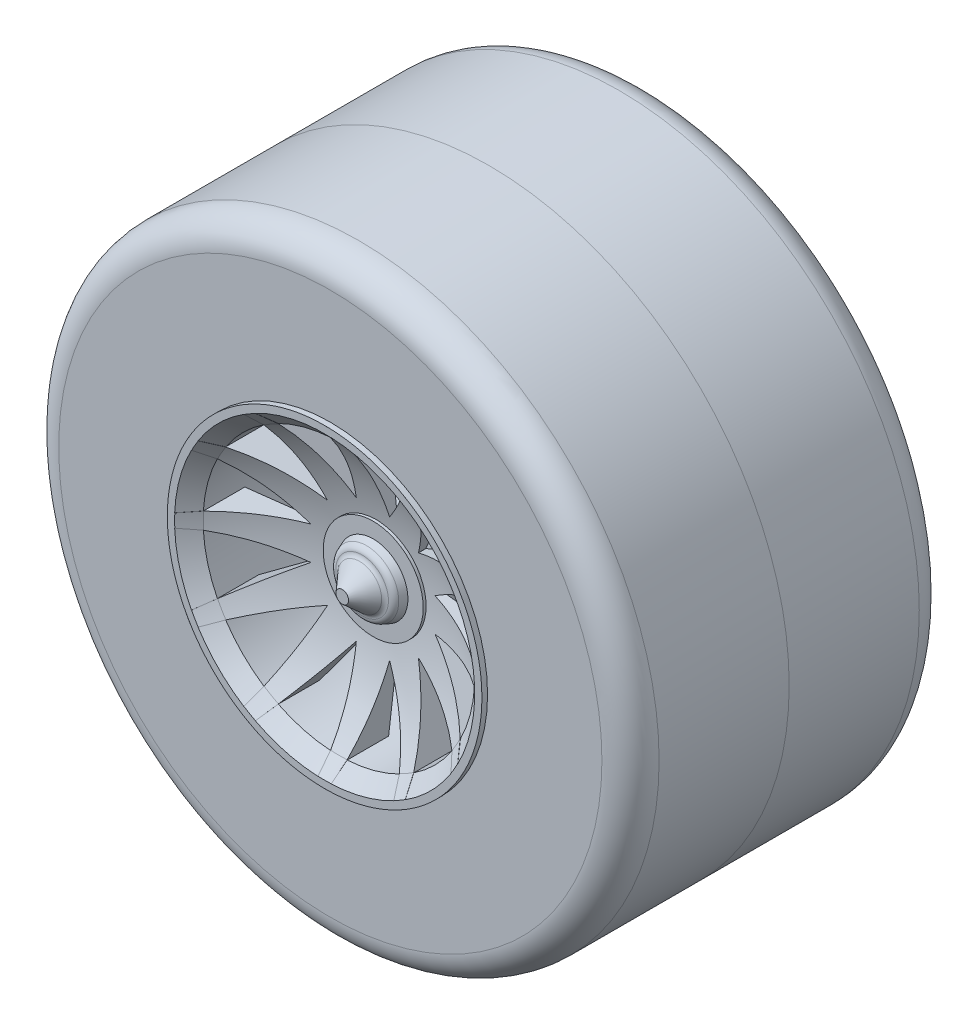
SolidWorks part; units mm, degrees
ref_plane "Front Plane" through (0, 0, 0) normal (0, 0, 1) x (1, 0, 0)
ref_plane "Top Plane" through (0, 0, 0) normal (0, 1, 0) x (1, 0, 0)
ref_plane "Right Plane" through (0, 0, 0) normal (1, 0, 0) x (0, 0, -1)
sketch "Sketch1" plane through (0, 0, 0) normal (1, 0, 0) x (0, 0, -1)
  line L0 (0, 0) -> (0, 21)
  line L1 (0, 21) -> (-9.1, 21)
  line L2 (-11.1, 19) -> (-11.1, 11)
  line L3 (-11.1, 11) -> (-11.5, 11)
  line L4 (-11.5, 11) -> (-11.5, 0)
  line L5 (-11.5, 0) -> (0, 0)
  arc A0 (-11.1, 19) -> (-9.1, 21) centre (-9.1, 19) cw
  dimension "D5" = 2
  dimension "D1" = 21
  dimension "D2" = 0.4
  dimension "D3" = 11.5
  dimension "D4" = 11
revolve "Revolve1" add sketch "Sketch1" angle 360 about L5
sketch "Sketch3" plane through (0, 0, 11.5) normal (0, 0, 1) x (1, 0, 0)
  circle A0 centre (0, 0) radius 9.5
  dimension "D1" = 19
extrude "Cut-Extrude3" cut sketch "Sketch3" against normal through all both and the other way through all
chamfer "Chamfer1" distance 1 angle 45 1 edges at (-9.5, 0, 11.5)
sketch "Sketch4" plane through (0, 0, 11.1) normal (0, 0, 1) x (1, 0, 0)
  line L0 (0, 4.5) -> (0, 21) construction
  line L1 (-0.4251, 10.8203) -> (-1.1632, 4.3471)
  line L2 (0.4251, 10.8203) -> (1.1632, 4.3471)
  line L3 (5.042, 9.5832) -> (1.1662, 4.3463)
  line L4 (5.7783, 9.1581) -> (3.1809, 3.1831)
  line L5 (9.1581, 5.7783) -> (3.1831, 3.1809)
  line L6 (9.5832, 5.042) -> (4.3463, 1.1662)
  line L7 (10.8203, 0.4251) -> (4.3471, 1.1632)
  line L8 (10.8203, -0.4251) -> (4.3471, -1.1632)
  line L9 (9.5832, -5.042) -> (4.3463, -1.1662)
  line L10 (9.1581, -5.7783) -> (3.1831, -3.1809)
  line L11 (5.7783, -9.1581) -> (3.1809, -3.1831)
  line L12 (5.042, -9.5832) -> (1.1662, -4.3463)
  line L13 (0.4251, -10.8203) -> (1.1632, -4.3471)
  line L14 (-0.4251, -10.8203) -> (-1.1632, -4.3471)
  line L15 (-5.042, -9.5832) -> (-1.1662, -4.3463)
  line L16 (-5.7783, -9.1581) -> (-3.1809, -3.1831)
  line L17 (-9.1581, -5.7783) -> (-3.1831, -3.1809)
  line L18 (-9.5832, -5.042) -> (-4.3463, -1.1662)
  line L19 (-10.8203, -0.4251) -> (-4.3471, -1.1632)
  line L20 (-10.8203, 0.4251) -> (-4.3471, 1.1632)
  line L21 (-9.5832, 5.042) -> (-4.3463, 1.1662)
  line L22 (-9.1581, 5.7783) -> (-3.2024, 3.1893)
  line L23 (-5.7783, 9.1581) -> (-3.1893, 3.2024)
  line L24 (-5.042, 9.5832) -> (-1.1662, 4.3463)
  arc A0 (-9.4089, 5.6984) -> (-9.6395, 5.2991) centre (0, 0) ccw
  arc A1 (-4.3463, 1.1662) -> (-4.3471, 1.1632) centre (0, 0) ccw
  circle A2 centre (0, 0) radius 21 construction
  arc A3 (-5.2991, 9.6395) -> (-5.6984, 9.4089) centre (0, 0) ccw
  arc A4 (0.2305, 10.9976) -> (-0.2305, 10.9976) centre (0, 0) ccw
  arc A5 (5.6984, 9.4089) -> (5.2991, 9.6395) centre (0, 0) ccw
  arc A6 (9.6395, 5.2991) -> (9.4089, 5.6984) centre (0, 0) ccw
  arc A7 (10.9976, -0.2305) -> (10.9976, 0.2305) centre (0, 0) ccw
  arc A8 (9.4089, -5.6984) -> (9.6395, -5.2991) centre (0, 0) ccw
  arc A9 (5.2991, -9.6395) -> (5.6984, -9.4089) centre (0, 0) ccw
  arc A10 (-0.2305, -10.9976) -> (0.2305, -10.9976) centre (0, 0) ccw
  arc A11 (-5.6984, -9.4089) -> (-5.2991, -9.6395) centre (0, 0) ccw
  arc A12 (-9.6395, -5.2991) -> (-9.4089, -5.6984) centre (0, 0) ccw
  arc A13 (-10.9976, 0.2305) -> (-10.9976, -0.2305) centre (0, 0) ccw
  arc A14 (-3.1809, 3.1831) -> (-3.1831, 3.1809) centre (0, 0) ccw
  arc A15 (-1.1632, 4.3471) -> (-1.1662, 4.3463) centre (0, 0) ccw
  arc A16 (1.1662, 4.3463) -> (1.1632, 4.3471) centre (0, 0) ccw
  arc A17 (3.1831, 3.1809) -> (3.1809, 3.1831) centre (0, 0) ccw
  arc A18 (4.3471, 1.1632) -> (4.3463, 1.1662) centre (0, 0) ccw
  arc A19 (-4.3471, -1.1632) -> (-4.3463, -1.1662) centre (0, 0) ccw
  arc A20 (-3.1831, -3.1809) -> (-3.1809, -3.1831) centre (0, 0) ccw
  arc A21 (-1.1662, -4.3463) -> (-1.1632, -4.3471) centre (0, 0) ccw
  arc A22 (1.1632, -4.3471) -> (1.1662, -4.3463) centre (0, 0) ccw
  arc A23 (3.1809, -3.1831) -> (3.1831, -3.1809) centre (0, 0) ccw
  arc A24 (4.3463, -1.1662) -> (4.3471, -1.1632) centre (0, 0) ccw
  arc A25 (-5.042, 9.5832) -> (-5.2991, 9.6395) centre (-5.2028, 9.4642) ccw
  arc A26 (-5.7783, 9.1581) -> (-5.6984, 9.4089) centre (-5.5948, 9.2378) cw
  arc A27 (-9.1581, 5.7783) -> (-9.4089, 5.6984) centre (-9.2378, 5.5948) ccw
  arc A28 (-9.5832, 5.042) -> (-9.6395, 5.2991) centre (-9.4642, 5.2028) cw
  arc A29 (-10.8203, 0.4251) -> (-10.9976, 0.2305) centre (-10.7976, 0.2264) ccw
  arc A30 (-10.8203, -0.4251) -> (-10.9976, -0.2305) centre (-10.7976, -0.2264) cw
  arc A31 (-9.5832, -5.042) -> (-9.6395, -5.2991) centre (-9.4642, -5.2028) ccw
  arc A32 (-9.1581, -5.7783) -> (-9.4089, -5.6984) centre (-9.2378, -5.5948) cw
  arc A33 (-5.7783, -9.1581) -> (-5.6984, -9.4089) centre (-5.5948, -9.2378) ccw
  arc A34 (-5.042, -9.5832) -> (-5.2991, -9.6395) centre (-5.2028, -9.4642) cw
  arc A35 (-0.4251, -10.8203) -> (-0.2305, -10.9976) centre (-0.2264, -10.7976) ccw
  arc A36 (0.4251, -10.8203) -> (0.2305, -10.9976) centre (0.2264, -10.7976) cw
  arc A37 (5.042, -9.5832) -> (5.2991, -9.6395) centre (5.2028, -9.4642) ccw
  arc A38 (5.7783, -9.1581) -> (5.6984, -9.4089) centre (5.5948, -9.2378) cw
  arc A39 (9.1581, -5.7783) -> (9.4089, -5.6984) centre (9.2378, -5.5948) ccw
  arc A40 (9.5832, -5.042) -> (9.6395, -5.2991) centre (9.4642, -5.2028) cw
  arc A41 (10.8203, -0.4251) -> (10.9976, -0.2305) centre (10.7976, -0.2264) ccw
  arc A42 (10.8203, 0.4251) -> (10.9976, 0.2305) centre (10.7976, 0.2264) cw
  arc A43 (9.5832, 5.042) -> (9.6395, 5.2991) centre (9.4642, 5.2028) ccw
  arc A44 (9.1581, 5.7783) -> (9.4089, 5.6984) centre (9.2378, 5.5948) cw
  arc A45 (5.7783, 9.1581) -> (5.6984, 9.4089) centre (5.5948, 9.2378) ccw
  arc A46 (5.042, 9.5832) -> (5.2991, 9.6395) centre (5.2028, 9.4642) cw
  arc A47 (0.4251, 10.8203) -> (0.2305, 10.9976) centre (0.2264, 10.7976) ccw
  arc A48 (-0.4251, 10.8203) -> (-0.2305, 10.9976) centre (-0.2264, 10.7976) cw
  arc A49 (-3.1893, 3.2024) -> (-3.2024, 3.1893) centre (-3.1984, 3.1984) cw
  point P57 (0, 0)
  point P101 (0.4054, 10.9925)
  point P104 (-0.4054, 10.9925)
  dimension "D1" = 22
  dimension "D2" = 9
  dimension "D4" = 0.2
  dimension "D5" = 0.01
  dimension "D3" = 12
extrude "Boss-Extrude1" add sketch "Sketch4" along normal blind 10 and the other way blind 3.5
sketch "Sketch5" plane through (0, 0, 0) normal (1, 0, 0) x (0, 0, -1)
  line L0 (0, 0) -> (-34.6228, 0) construction
  line L1 (-10.5, 9.4824) -> (-11.5, 10.4898)
  line L2 (-11.5, 10.4898) -> (-11.5, 10.9976)
  line L3 (-11.5, 10.9976) -> (-11.8812, 11.6153)
  line L4 (-11.8812, 11.6153) -> (-21.6946, 11.6153)
  line L5 (-21.6946, 11.6153) -> (-21.6946, 0)
  line L6 (-21.6946, 0) -> (-7.5497, 0)
  spline S0 degree 2 poles (-10.5, 9.4824) (-7.6252, 5.7251) (-7.5497, 0) knots 0 0 0 1 1 1
revolve "Cut-Revolve1" cut sketch "Sketch5" angle 360 about L6
sketch "Sketch6" plane through (0, 0, 0) normal (1, 0, 0) x (0, 0, -1)
  line L0 (0, 0) -> (-21.6266, 0) construction
  line L1 (0, -21) -> (0, 21) construction
  line L2 (-7.4322, 0) -> (-7.9181, 2.5)
  line L3 (-7.9181, 2.5) -> (-8.8749, 2.128)
  line L4 (-8.8749, 2.128) -> (-8.8749, 1.6817)
  line L5 (-8.8749, 1.6817) -> (-10.2635, 0.4419)
  line L6 (-10.2635, 0.4419) -> (-10.2635, 0)
  line L7 (-10.2635, 0) -> (-7.4322, 0)
  dimension "D1" = 2.5
  dimension "D2" = 101
revolve "Revolve2" add sketch "Sketch6" angle 360 about L0
fillet "Fillet1" radius 0.5 1 edges at (-1.6817, 0, 8.8749)
fillet "Fillet2" radius 0.5 1 edges at (-2.128, 0, 8.8749)
mirror "Mirror1" about plane through (0, 0, 0) normal (0, 0, 1) of bodies 104 105
sketch "Sketch7" plane through (0, 0, 11.1) normal (0, 0, 1) x (1, 0, 0)
  circle A0 centre (0, 0) radius 3.5
  dimension "D1" = 7
extrude "Boss-Extrude2" add sketch "Sketch7" against normal blind 15 from offset 3 offset against normal yes
sketch "Sketch8" plane through (0, 0, -11.1) normal (0, 0, -1) x (-1, 0, 0)
  circle A0 centre (0, 0) radius 2.5
  dimension "D1" = 5
extrude "Cut-Extrude4" cut sketch "Sketch8" against normal blind 5
